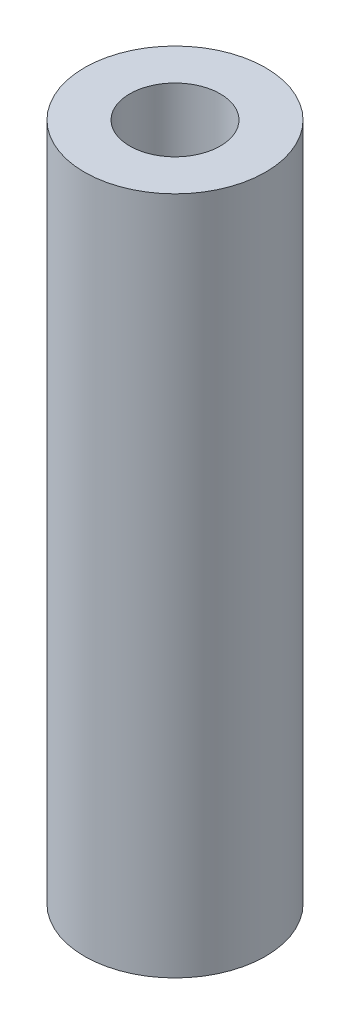
SolidWorks part; units mm, degrees
ref_plane "Front Plane" through (0, 0, 0) normal (0, 0, 1) x (1, 0, 0)
ref_plane "Top Plane" through (0, 0, 0) normal (0, 1, 0) x (1, 0, 0)
ref_plane "Right Plane" through (0, 0, 0) normal (1, 0, 0) x (0, 0, -1)
sketch "Sketch1" plane through (0, 0, 0) normal (0, 1, 0) x (1, 0, 0)
  circle A0 centre (0, 0) radius 2.54
  circle A1 centre (0, 0) radius 5.08
  dimension "D1" = 5.08
  dimension "D2" = 10.16
extrude "Boss-Extrude1" add sketch "Sketch1" along normal blind 38.1
